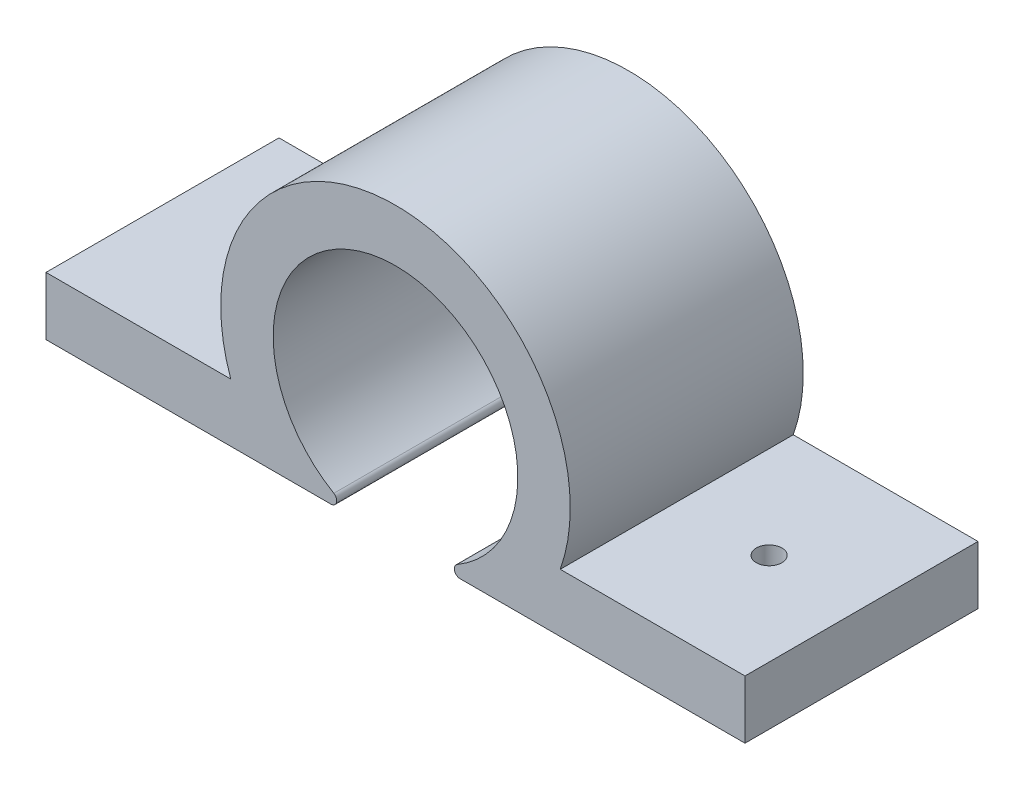
SolidWorks part; units mm, degrees
material "PVC 0.007 Plasticized"
ref_plane "Front Plane" through (0, 0, 0) normal (0, 0, 1) x (1, 0, 0)
ref_plane "Top Plane" through (0, 0, 0) normal (0, 1, 0) x (1, 0, 0)
ref_plane "Right Plane" through (0, 0, 0) normal (1, 0, 0) x (0, 0, -1)
sketch "Sketch1" plane through (0, 0, 0) normal (0, 0, 1) x (1, 0, 0)
  line L0 (14.1421, 2.5) -> (30, 2.5)
  line L1 (-30, 2.5) -> (-14.1421, 2.5)
  line L2 (-30, 2.5) -> (-30, -2.5)
  line L3 (-30, -2.5) -> (30, -2.5)
  line L4 (30, 2.5) -> (30, -2.5)
  line L5 (-30, 2.5) -> (30, -2.5) construction
  line L6 (-30, -2.5) -> (30, 2.5) construction
  arc A0 (14.1421, 2.5) -> (-14.1421, 2.5) centre (0, 7.5) ccw
  point P0 (0, 0)
  point P9 (0, -2.5)
  dimension "D3" = 30
  dimension "D1" = 60
  dimension "D2" = 5
  dimension "D4" = 10
sketch "Sketch2" plane through (0, 0, 0) normal (0, 0, 1) x (1, 0, 0)
  line L1 (-30, 2.5) -> (-14.1421, 2.5) construction
  circle A0 centre (0, 7.5) radius 15 construction
  point P0 (-14.1421, 2.5)
  point P1 (14.1421, 2.5)
extrude "Boss-Extrude1" add sketch "Sketch1" along normal blind 20
sketch "Sketch3" plane through (0, 0, 20) normal (0, 0, 1) x (1, 0, 0)
  circle A0 centre (0, 7.5) radius 10.5
  arc A1 (14.1421, 2.5) -> (-14.1421, 2.5) centre (0, 7.5) ccw construction
  point P0 (0, 7.5)
  dimension "D1" = 21
extrude "Cut-Extrude1" cut sketch "Sketch3" against normal through all
sketch "Sketch4" plane through (0, 2.5, 0) normal (0, 1, 0) x (1, 0, 0)
  line L0 (-14.1421, 0) -> (-30, 0) construction
  line L1 (-30, -20) -> (-30, 0) construction
  line L2 (30, 0) -> (14.1421, 0) construction
  circle A0 centre (-22.0711, -10) radius 1.1
  circle A1 centre (22.0711, -10) radius 1.1
  point P7 (-22.0711, 0)
  point P10 (-30, -10)
  point P14 (22.0711, 0)
  dimension "D1" = 2.2
extrude "Cut-Extrude2" cut sketch "Sketch4" against normal up to surface (5 mm away) up to face at (-16.6008, -2.5, 10)
fillet "Fillet1" radius 0.5 2 edges at (3.2016, -2.5, 10) (-3.2016, -2.5, 10)
